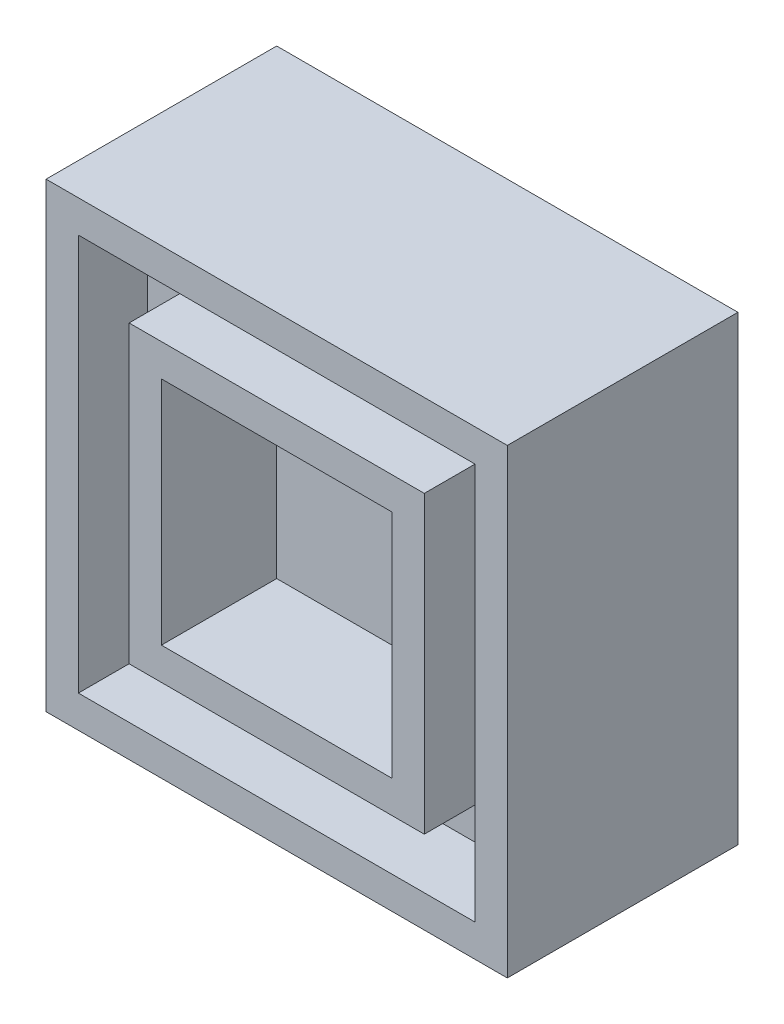
SolidWorks part; units mm, degrees
ref_plane "正面" through (0, 0, 0) normal (0, 0, 1) x (1, 0, 0)
ref_plane "平面" through (0, 0, 0) normal (0, 1, 0) x (1, 0, 0)
ref_plane "右側面" through (0, 0, 0) normal (1, 0, 0) x (0, 0, -1)
sketch "ｽｹｯﾁ1" plane through (0, 0, 0) normal (0, 0, 1) x (1, 0, 0)
  line L1 (-10, -10) -> (10, -10)
  line L2 (-10, -10) -> (-10, 10)
  line L3 (-10, 10) -> (10, 10)
  line L4 (10, -10) -> (10, 10)
  line L5 (-10, -10) -> (10, 10) construction
  line L6 (-10, 10) -> (10, -10) construction
  point P0 (0, 0)
  dimension "D1" = 20
  dimension "D2" = 20
extrude "ﾎﾞｽ - 押し出し1" add sketch "ｽｹｯﾁ1" along normal blind 10
shell "ｼｪﾙ1" thickness 5
sketch "ｽｹｯﾁ2" plane through (0, 0, 10) normal (0, 0, 1) x (1, 0, 0)
  line L1 (-6.5, -6.5) -> (6.5, -6.5)
  line L2 (-6.5, -6.5) -> (-6.5, 6.5)
  line L3 (-6.5, 6.5) -> (6.5, 6.5)
  line L4 (6.5, -6.5) -> (6.5, 6.5)
  line L5 (-6.5, -6.5) -> (6.5, 6.5) construction
  line L6 (-6.5, 6.5) -> (6.5, -6.5) construction
  line L7 (-8.5, -8.5) -> (8.5, -8.5)
  line L8 (-8.5, -8.5) -> (-8.5, 8.5)
  line L9 (-8.5, 8.5) -> (8.5, 8.5)
  line L10 (8.5, -8.5) -> (8.5, 8.5)
  line L11 (-8.5, -8.5) -> (8.5, 8.5) construction
  line L12 (-8.5, 8.5) -> (8.5, -8.5) construction
  point P0 (0, 0)
  point P6 (0, 0)
  dimension "D1" = 13
  dimension "D2" = 17
  dimension "D3" = 17
extrude "ﾎﾞｽ - 押し出し2" [suppressed] add sketch "ｽｹｯﾁ2" along normal blind 3
sketch "ｽｹｯﾁ3" plane through (0, 0, 10) normal (0, 0, 1) x (1, 0, 0)
  line L1 (-6.4, -6.4) -> (6.4, -6.4)
  line L2 (-6.4, -6.4) -> (-6.4, 6.4)
  line L3 (-6.4, 6.4) -> (6.4, 6.4)
  line L4 (6.4, -6.4) -> (6.4, 6.4)
  line L5 (-6.4, -6.4) -> (6.4, 6.4) construction
  line L6 (-6.4, 6.4) -> (6.4, -6.4) construction
  line L7 (-8.6, -8.6) -> (8.6, -8.6)
  line L8 (-8.6, -8.6) -> (-8.6, 8.6)
  line L9 (-8.6, 8.6) -> (8.6, 8.6)
  line L10 (8.6, -8.6) -> (8.6, 8.6)
  line L11 (-8.6, -8.6) -> (8.6, 8.6) construction
  line L12 (-8.6, 8.6) -> (8.6, -8.6) construction
  point P1 (0, 0)
  point P6 (0, 0)
  dimension "D1" = 12.8
  dimension "D2" = 17.2
extrude "ｶｯﾄ - 押し出し1" cut sketch "ｽｹｯﾁ3" against normal blind 3
